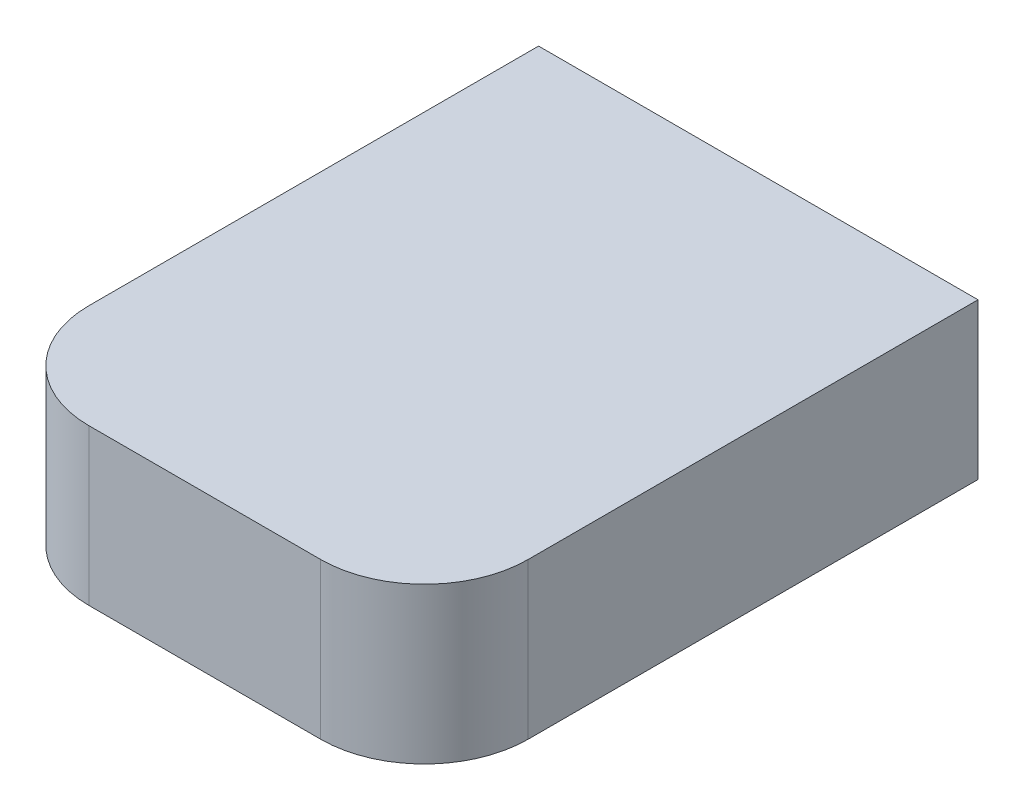
SolidWorks part; units mm, degrees
ref_plane "Alzado" through (0, 0, 0) normal (0, 0, 1) x (1, 0, 0)
ref_plane "Planta" through (0, 0, 0) normal (0, 1, 0) x (1, 0, 0)
ref_plane "Vista lateral" through (0, 0, 0) normal (1, 0, 0) x (0, 0, -1)
sketch "Sketch1" plane through (0, 0, 0) normal (0, 0, 1) x (1, 0, 0)
  line L0 (134.3, 0) -> (-12.7, 0) construction
  line L1 (129.05, -4.5) -> (116.35, -4.5)
  line L2 (129.05, -4.5) -> (129.05, 0)
  line L3 (129.05, 0) -> (116.35, 0)
  line L4 (116.35, -4.5) -> (116.35, 0)
  line L5 (134.3, -4.5) -> (-12.7, -4.5) construction
  dimension "D1" = 6.35
  dimension "D2" = 12.7
extrude "Boss-Extrude1" add sketch "Sketch1" along normal blind 16
fillet "Fillet1" radius 3 1 edges at (129.05, -2.25, 16)
fillet "Fillet2" radius 3 1 edges at (116.35, -2.25, 16)
